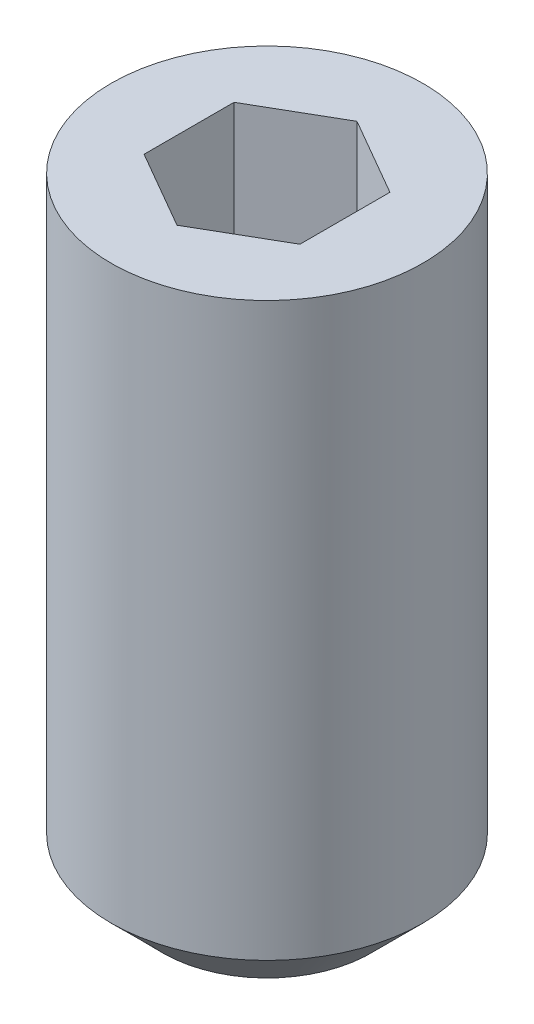
SolidWorks part; units mm, degrees
ref_plane "Front Plane" through (0, 0, 0) normal (0, 0, 1) x (1, 0, 0)
ref_plane "Top Plane" through (0, 0, 0) normal (0, 1, 0) x (1, 0, 0)
ref_plane "Right Plane" through (0, 0, 0) normal (1, 0, 0) x (0, 0, -1)
sketch "Sketch1" plane through (0, 0, 0) normal (0, 0, 1) x (1, 0, 0)
  line L0 (0, 6) -> (0, 0) construction
  line L1 (0, 6) -> (1.5, 6)
  line L2 (1.5, 6) -> (1.5, 0)
  line L3 (1.5, 0) -> (0, 0)
  line L4 (0, 6) -> (0, 0)
  dimension "TPC" = 3
  dimension "SLH" = 6
revolve "Revolve1" add sketch "Sketch1" angle 360 about L0
cosmetic thread "Cosmetic Thread1" parameters "SS_D1_s"=2.439
sketch "Sketch2" plane through (0, 0, 0) normal (0, 0, 1) x (1, 0, 0)
  line L0 (0, 6) -> (0, 4.367) construction
  line L1 (0, 6) -> (0.75, 6)
  line L2 (0.75, 6) -> (0.75, 4.8)
  line L3 (0.75, 4.8) -> (0, 4.367)
  line L4 (0, 6) -> (0, 4.367)
  line L5 (1.5, 6) -> (-1.5, 6) construction
  dimension "D3" = 60
  dimension "SS_C" = 1.2
  dimension "SS_B" = 1.5
revolve "Cut-Revolve1" cut sketch "Sketch2" angle 360 about L0
sketch "Sketch3" plane through (0, 6, 0) normal (0, 1, 0) x (1, 0, 0)
  line L1 (0, 0.866) -> (-0.75, 0.433)
  line L2 (-0.75, 0.433) -> (-0.75, -0.433)
  line L3 (-0.75, -0.433) -> (0, -0.866)
  line L4 (0, -0.866) -> (0.75, -0.433)
  line L5 (0.75, -0.433) -> (0.75, 0.433)
  line L6 (0.75, 0.433) -> (0, 0.866)
  circle A0 centre (0, 0) radius 0.75 construction
  circle A1 centre (0, 0) radius 0.75 construction
extrude "Cut-Extrude1" cut sketch "Sketch3" against normal blind 1.2
sketch "Sketch4" plane through (0, 0, 0) normal (0, 0, 1) x (1, 0, 0)
  line L0 (1, 0) -> (1.5, 0)
  line L1 (1.5, 0) -> (1.5, 0.5)
  line L2 (1.5, 0.5) -> (1, 0)
  line L4 (-1.5, 0) -> (1.5, 0) construction
  line L5 (0, 0) -> (0, 6) construction
  line L6 (1.5, 6) -> (-1.5, 6) construction
  line L7 (1.5, 6) -> (1.5, 0) construction
  dimension "D1" = 45
  dimension "SS_D_s" = 2
revolve "Cut-Revolve2" cut sketch "Sketch4" angle 360 about L5
